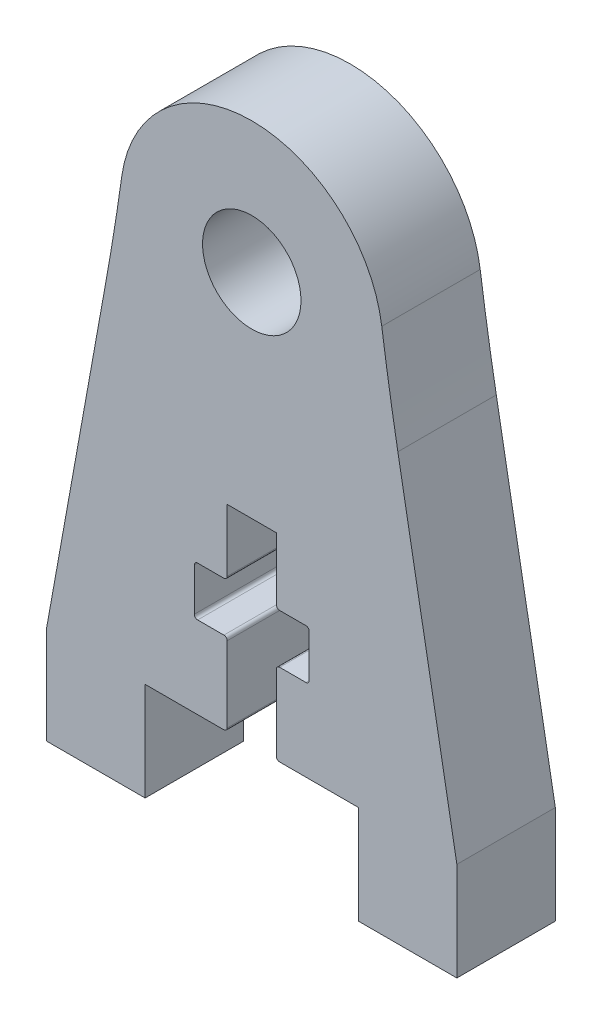
SolidWorks part; units mm, degrees
ref_plane "Front Plane" through (0, 0, 0) normal (0, 0, 1) x (1, 0, 0)
ref_plane "Top Plane" through (0, 0, 0) normal (0, 1, 0) x (1, 0, 0)
ref_plane "Right Plane" through (0, 0, 0) normal (1, 0, 0) x (0, 0, -1)
sketch "Sketch2" plane through (0, 0, 0) normal (0, 0, 1) x (1, 0, 0)
  line L0 (0, 0) -> (-25, 0)
  line L1 (-25, 0) -> (-20.5, 25)
  line L2 (-4.5, 25) -> (0, 0)
  line L3 (-4.5, 25) -> (-20.5, 25) construction
  arc A0 (-20.5, 25) -> (-4.5, 25) centre (-12.5, 25) cw
  circle A1 centre (-12.5, 25) radius 3
  point P7 (-12.5, 0)
  point P8 (0, 15.5702)
  point P9 (-1.0905, 15.8125)
  point P10 (-2.4234, 12.7833)
  point P11 (-12.5, 25)
  point P12 (0, 0)
  point P13 (-2.5445, 16.5395)
  dimension "D1" = 6
  dimension "D2" = 8
  dimension "D3" = 25
  dimension "D4" = 25
extrude "Boss-Extrude1" add sketch "Sketch2" along normal blind 6
fillet "Fillet1" radius 160 2 edges at (-20.5, 25, 3) (-4.5, 25, 3)
sketch "Sketch4" plane through (0, 0, 6) normal (0, 0, 1) x (1, 0, 0)
  line L0 (-14, 0) -> (-14, 4.8)
  line L1 (-25, 0) -> (0, 0) construction
  line L2 (-14.2, 5) -> (-15.8, 5)
  line L3 (-16, 5.2) -> (-16, 7.8)
  line L4 (-15.8, 8) -> (-14.2, 8)
  line L5 (-14, 8.2) -> (-14, 12)
  line L6 (-14, 12) -> (-11, 12)
  line L7 (-11, 12) -> (-11, 8.2)
  line L8 (-10.8, 8) -> (-9.2, 8)
  line L9 (-9, 7.8) -> (-9, 5.2)
  line L10 (-9.2, 5) -> (-10.8, 5)
  line L11 (-11, 4.8) -> (-11, 0)
  line L12 (-14, 0) -> (-11, 0)
  line L13 (-16, 6.5) -> (-9, 6.5) construction
  arc A0 (-9, 5.2) -> (-9.2, 5) centre (-9.2, 5.2) cw
  arc A1 (-9, 7.8) -> (-9.2, 8) centre (-9.2, 7.8) ccw
  arc A2 (-16, 7.8) -> (-15.8, 8) centre (-15.8, 7.8) cw
  arc A3 (-16, 5.2) -> (-15.8, 5) centre (-15.8, 5.2) ccw
  arc A4 (-14.2, 8) -> (-14, 8.2) centre (-14.2, 8.2) ccw
  arc A5 (-11, 8.2) -> (-10.8, 8) centre (-10.8, 8.2) ccw
  arc A6 (-10.8, 5) -> (-11, 4.8) centre (-10.8, 4.8) ccw
  arc A7 (-14, 4.8) -> (-14.2, 5) centre (-14.2, 4.8) ccw
  point P14 (-12.5, 0)
  point P16 (-12.5, 0)
  point P18 (-12.5, 6.5)
  point P19 (0, 0)
  point P20 (0, 0)
  point P27 (-16, 8)
  point P30 (-16, 5)
  point P39 (-14, 5)
  dimension "D6" = 0.2
  dimension "D1" = 7
  dimension "D2" = 3
  dimension "D3" = 3
  dimension "D4" = 5
  dimension "D5" = 12
extrude "Groove" cut sketch "Sketch4" against normal through all
sketch "Sketch5" plane through (0, 0, 0) normal (0, -1, 0) x (1, 0, 0)
  line L0 (-25, 0) -> (-14, 0) construction
  line L1 (-25, 6) -> (-19, 6)
  line L2 (-25, 6) -> (-25, 0)
  line L3 (-25, 0) -> (-19, 0)
  line L4 (-19, 6) -> (-19, 0)
  line L5 (-11, 0) -> (0, 0) construction
  line L6 (0, 6) -> (-6, 6)
  line L7 (0, 6) -> (0, 0)
  line L8 (0, 0) -> (-6, 0)
  line L9 (-6, 6) -> (-6, 0)
  dimension "D1" = 6
extrude "Fingers" add sketch "Sketch5" along normal blind 6
fillet "Fillet2" radius 0.2 2 edges at (-11, 0, 3) (-14, 0, 3)
